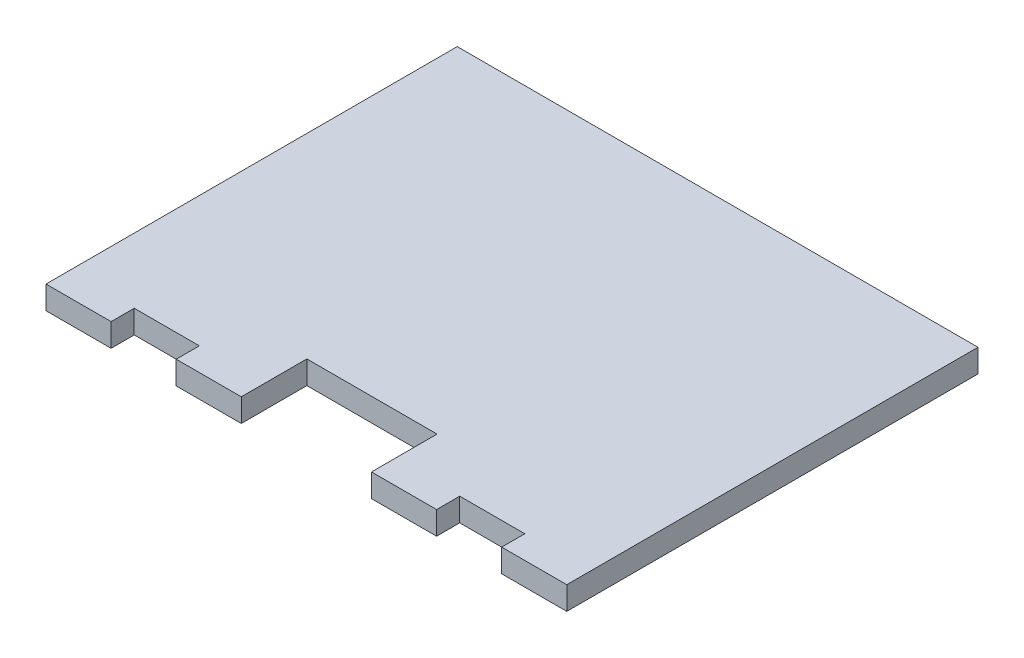
SolidWorks part; units mm, degrees
ref_plane "Front Plane" through (0, 0, 0) normal (0, 0, 1) x (1, 0, 0)
ref_plane "Top Plane" through (0, 0, 0) normal (0, 1, 0) x (1, 0, 0)
ref_plane "Right Plane" through (0, 0, 0) normal (1, 0, 0) x (0, 0, -1)
sketch "Sketch1" plane through (0, 0, 0) normal (0, 1, 0) x (1, 0, 0)
  line L1 (-157.9727, 43.1681) -> (99.215, 43.1681)
  line L2 (-157.9727, 43.1681) -> (-157.9727, -159.9252)
  line L3 (-157.9727, -159.9252) -> (99.215, -159.9252)
  line L4 (99.215, 43.1681) -> (99.215, -159.9252)
  dimension "D1" = 203.0933
  dimension "D2" = 257.1877
extrude "Boss-Extrude1" add sketch "Sketch1" along normal blind 11.43
sketch "Sketch2" plane through (0, 0, 0) normal (0, -1, 0) x (1, 0, 0)
  line L0 (-157.9727, 159.9252) -> (99.215, 159.9252) construction
  line L1 (-125.8242, 159.9252) -> (-93.6758, 159.9252)
  line L2 (-125.8242, 159.9252) -> (-125.8242, 148.4952)
  line L3 (-125.8242, 148.4952) -> (-93.6758, 148.4952)
  line L4 (-93.6758, 159.9252) -> (-93.6758, 148.4952)
  line L5 (-29.3788, 159.9252) -> (-29.3788, -43.1681) construction
  line L6 (99.215, -43.1681) -> (-157.9727, -43.1681) construction
  line L7 (-157.9727, -43.1681) -> (-157.9727, 159.9252) construction
  line L8 (2.7696, 159.9252) -> (-61.5273, 159.9252)
  line L9 (-29.3788, 159.9252) -> (-29.3788, 127.5402)
  line L10 (2.7696, 127.5402) -> (-61.5273, 127.5402)
  line L11 (-61.5273, 159.9252) -> (-61.5273, 127.5402)
  line L12 (2.7696, 159.9252) -> (2.7696, 127.5402)
  line L13 (67.0666, 148.4952) -> (34.9181, 148.4952)
  line L14 (34.9181, 159.9252) -> (34.9181, 148.4952)
  line L15 (67.0666, 159.9252) -> (34.9181, 159.9252)
  line L16 (67.0666, 159.9252) -> (67.0666, 148.4952)
  line M6 (99.215, 159.9252) -> (-157.9727, 159.9252)
  dimension "D1" = 11.43
  dimension "D2" = 32.385
  dimension "D3" = 32.1485
  dimension "D4" = 32.1485
  dimension "D6" = 32.1485
  dimension "D5" = 32.1485
extrude "Cut-Extrude1" cut sketch "Sketch2" against normal through all contours L4 L2 L3 M6 | L8 L11 L10 L9 | L12 L9 L10 M6 | L16 L14 L13 M6
equation "\"D1@Sketch1\"=\"Side Height@Assembled Container.Assembly\""
equation "\"D2@Sketch1\"=\"Short Side Width@Assembled Container.Assembly\""
equation "\"D1@Boss-Extrude1\"=\"Acrylic Thickness@Assembled Container.Assembly\""
equation "\"D1@Sketch2\"=\"Acrylic Thickness@Assembled Container.Assembly\""
equation "\"D2@Sketch2\" = \"Short Side Finger Hole@Assembled Container.Assembly\""
equation "\"D3@Sketch2\"=\"Lid Short Side Outer Cutout@Assembled Container.Assembly\""
equation "\"D4@Sketch2\"=\"Lid Short Side Outer Overhang@Assembled Container.Assembly\""
equation "\"D5@Sketch2\"=\"Lid Short Side Middle Overhang@Assembled Container.Assembly\""
